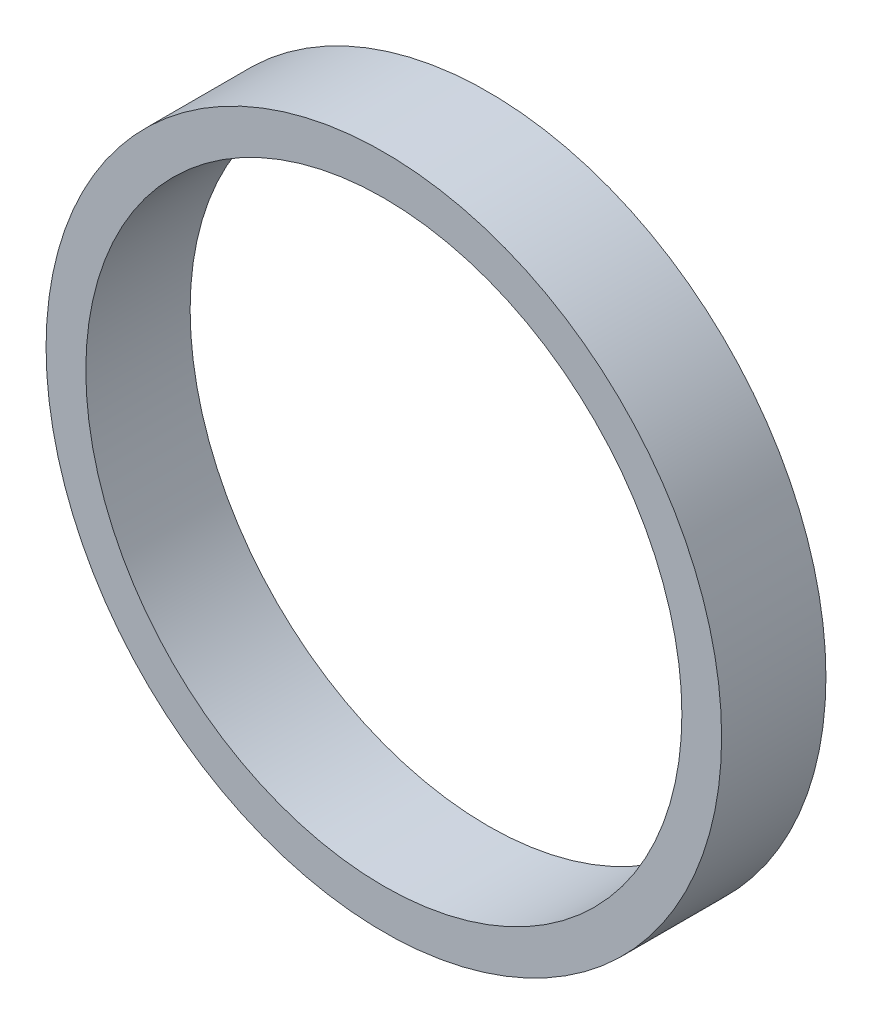
SolidWorks part; units mm, degrees
ref_plane "前视基准面" through (0, 0, 0) normal (0, 0, 1) x (1, 0, 0)
ref_plane "上视基准面" through (0, 0, 0) normal (0, 1, 0) x (1, 0, 0)
ref_plane "右视基准面" through (0, 0, 0) normal (1, 0, 0) x (0, 0, -1)
sketch "草图1" plane through (0, 0, 0) normal (0, 0, 1) x (1, 0, 0)
  circle A0 centre (0, 0) radius 30
  circle A1 centre (0, 0) radius 34
  dimension "D1" = 60
  dimension "D2" = 68
extrude "凸台-拉伸1" add sketch "草图1" along normal blind 10.5
